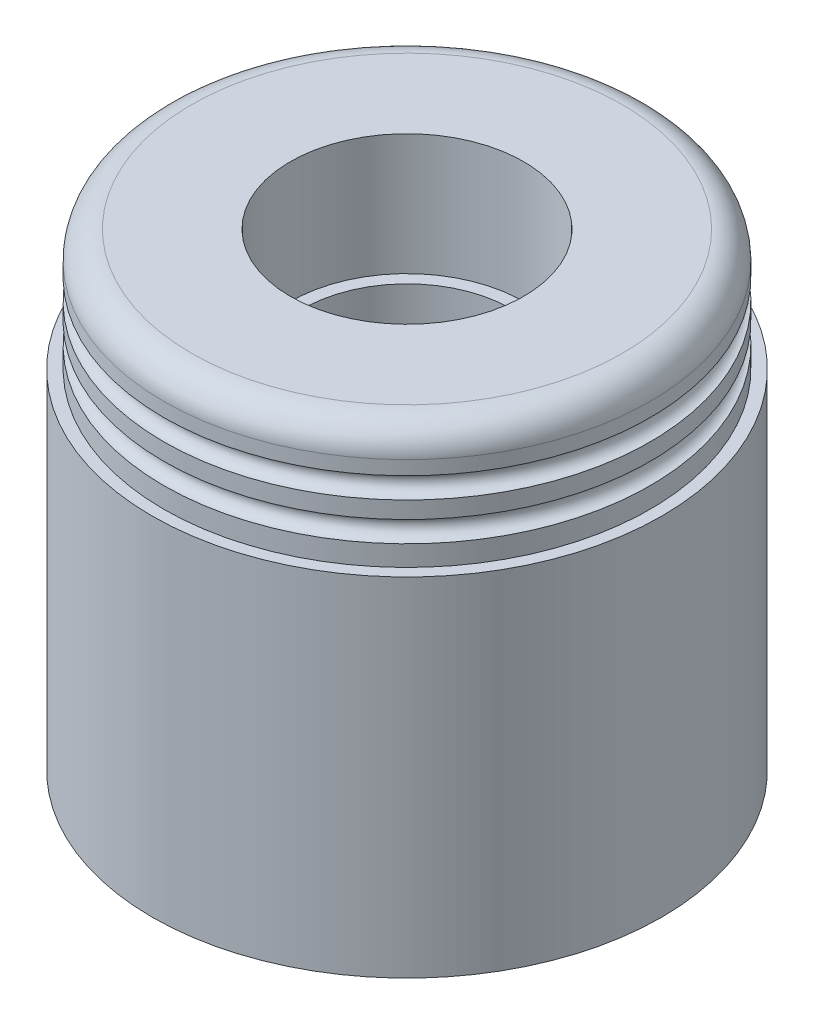
SolidWorks part; units mm, degrees
ref_plane "Front Plane" through (0, 0, 0) normal (0, 0, 1) x (1, 0, 0)
ref_plane "Top Plane" through (0, 0, 0) normal (0, 1, 0) x (1, 0, 0)
ref_plane "Right Plane" through (0, 0, 0) normal (1, 0, 0) x (0, 0, -1)
sketch "Sketch1" plane through (0, 0, 0) normal (0, 1, 0) x (1, 0, 0)
  circle A0 centre (0, 0) radius 4.7625
  circle A1 centre (0, 0) radius 11.6459
  dimension "D1" = 9.525
  dimension "D2" = 23.2918
extrude "lower" add sketch "Sketch1" along normal blind 15.875
sketch "Sketch2" plane through (0, 15.875, 0) normal (0, 1, 0) x (1, 0, 0)
  circle A0 centre (0, 0) radius 11.1125
  circle A1 centre (0, 0) radius 5.334
  dimension "D1" = 22.225
  dimension "D2" = 10.668
extrude "seat" add sketch "Sketch2" along normal blind 5.5372 separate body
fillet "Fillet1" radius 1.27 1 edges at (0, 21.4122, 11.1125)
sketch "Sketch3" plane through (0, 0, 0) normal (0, 0, 1) x (1, 0, 0)
  line L0 (-11.1125, 20.1422) -> (-11.1125, 19.5039)
  line L1 (-11.1125, 20.1422) -> (-11.1125, 15.875) construction
  line L2 (-11.1125, 18.5436) -> (-11.1125, 17.7711)
  line L3 (-11.1125, 16.8108) -> (-11.1125, 15.875)
  line L4 (-11.1125, 15.875) -> (-12.695, 15.875)
  line L5 (-12.695, 15.875) -> (-12.695, 20.1422)
  line L6 (-12.695, 20.1422) -> (-11.1125, 20.1422)
  line L7 (0, 0) -> (0, 2.0879) construction
  line L8 (0, 0) -> (0, 26.9755) construction
  arc A0 (-11.1125, 18.5436) -> (-11.1125, 19.5039) centre (-11.1125, 19.0238) ccw
  arc A1 (-11.1125, 16.8108) -> (-11.1125, 17.7711) centre (-11.1125, 17.2909) ccw
revolve "Cut-Revolve1" cut sketch "Sketch3" angle 360 about L8
